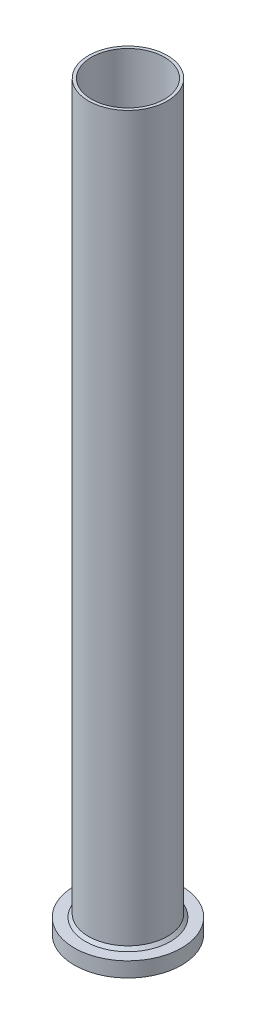
SolidWorks part; units mm, degrees
ref_plane "Front Plane" through (0, 0, 0) normal (0, 0, 1) x (1, 0, 0)
ref_plane "Top Plane" through (0, 0, 0) normal (0, 1, 0) x (1, 0, 0)
ref_plane "Right Plane" through (0, 0, 0) normal (1, 0, 0) x (0, 0, -1)
sketch "Sketch1" plane through (0, 0, 0) normal (0, 1, 0) x (1, 0, 0)
  line L7 (8.0829, -14) -> (16.1658, 0)
  line L8 (16.1658, 0) -> (8.0829, 14)
  line L9 (8.0829, 14) -> (-8.0829, 14)
  line L10 (-8.0829, 14) -> (-16.1658, 0)
  line L11 (-16.1658, 0) -> (-8.0829, -14)
  line L12 (-8.0829, -14) -> (8.0829, -14)
  circle A0 centre (0, 0) radius 14 construction
  circle A1 centre (0, 0) radius 18
  dimension "D2" = 36
  dimension "D1" = 28
extrude "Boss-Extrude1" add sketch "Sketch1" along normal blind 4
sketch "Sketch2" plane through (0, 4, 0) normal (0, 1, 0) x (1, 0, 0)
  circle A0 centre (0, 0) radius 12.25
  circle A1 centre (0, 0) radius 13.25
  dimension "D1" = 24.5
  dimension "D2" = 26.5
extrude "Boss-Extrude2" add sketch "Sketch2" along normal blind 245 separate body
sketch "Sketch3" plane through (0, 4, 0) normal (0, 1, 0) x (1, 0, 0)
  circle A0 centre (0, 0) radius 18 construction
  circle A1 centre (0, 0) radius 18
  circle A2 centre (0, 0) radius 12.25 construction
  circle A3 centre (0, 0) radius 12.25
extrude "Boss-Extrude3" add sketch "Sketch3" along normal blind 1
chamfer "Chamfer1" distance 1 angle 45 1 edges at (0, 5, 13.25)
